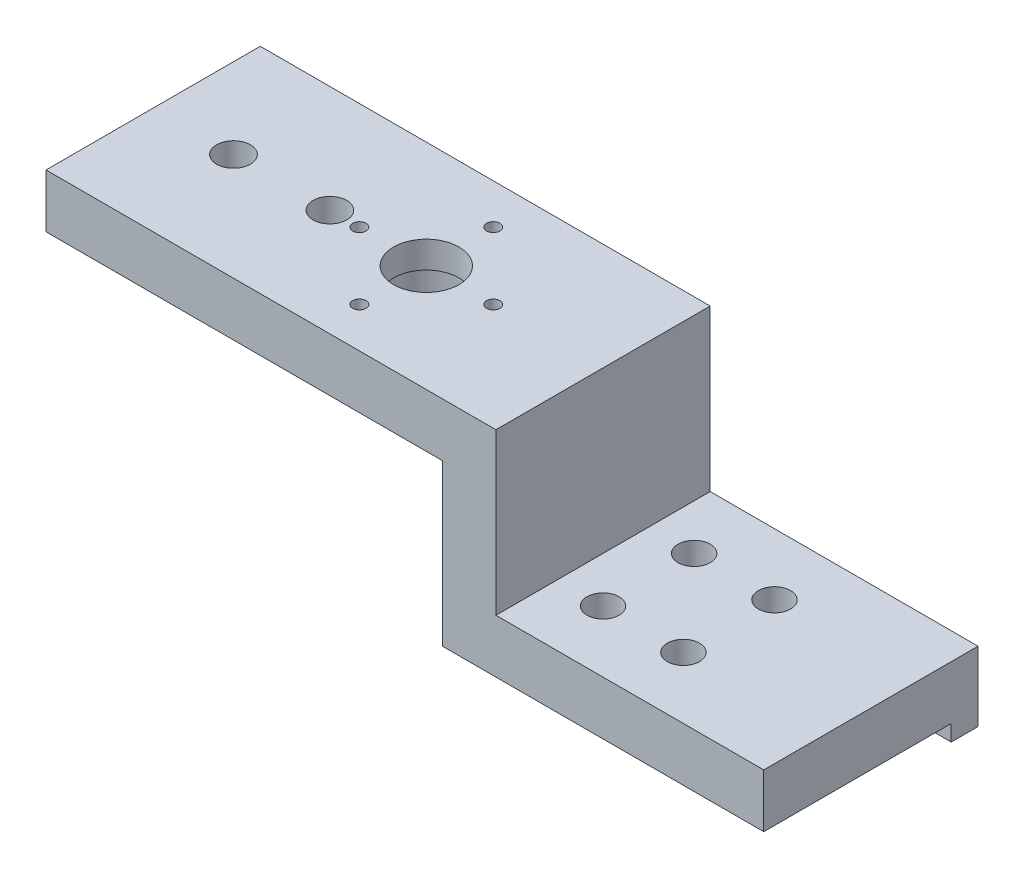
SolidWorks part; units mm, degrees
material "3.0205 (EN-AW 1200)"
ref_plane "Front Plane" through (0, 0, 0) normal (0, 0, 1) x (1, 0, 0)
ref_plane "Top Plane" through (0, 0, 0) normal (0, 1, 0) x (1, 0, 0)
ref_plane "Right Plane" through (0, 0, 0) normal (1, 0, 0) x (0, 0, -1)
sketch "Sketch1" plane through (0, 0, 0) normal (0, 1, 0) x (1, 0, 0)
  line L1 (-30, -20) -> (30, -20)
  line L2 (-30, -20) -> (-30, 20)
  line L3 (-30, 20) -> (30, 20)
  line L4 (30, -20) -> (30, 20)
  line L5 (0, 20) -> (0, -20) construction
  line L6 (-30, 0) -> (30, 0) construction
  point P0 (0, 0)
  dimension "D1" = 40
  dimension "D2" = 60
extrude "Boss-Extrude1" add sketch "Sketch1" along normal blind 10 contours L3 L4 L1 L2
sketch "Sketch2" plane through (0, 10, 0) normal (0, 1, 0) x (1, 0, 0)
  line L1 (-20, -20) -> (-30, -20)
  line L2 (-20, -20) -> (-20, 20)
  line L3 (-20, 20) -> (-30, 20)
  line L4 (-30, -20) -> (-30, 20)
  line L5 (-25, 20) -> (-25, -20) construction
  line L6 (-20, 0) -> (-30, 0) construction
  point P0 (-25, 0)
  dimension "D1" = 10
extrude "Boss-Extrude2" add sketch "Sketch2" along normal blind 30
sketch "Sketch3" plane through (-30, 0, 0) normal (-1, 0, 0) x (0, 0, 1)
  line L0 (-20, 40) -> (-20, 0) construction
  line L1 (-20, 30) -> (20, 30)
  line L2 (-20, 30) -> (-20, 40)
  line L3 (-20, 40) -> (20, 40)
  line L4 (20, 30) -> (20, 40)
  line L5 (0, 40) -> (0, 30) construction
  line L6 (-20, 35) -> (20, 35) construction
  point P0 (0, 35)
  dimension "D1" = 10
extrude "Boss-Extrude3" add sketch "Sketch3" along normal blind 74
sketch "Sketch4" plane through (0, 30, 0) normal (0, -1, 0) x (1, 0, 0)
  line L0 (-30, -20) -> (-30, 20) construction
  circle A0 centre (-53, 0) radius 6.1
  circle A1 centre (-71, 0) radius 3.15
  circle A2 centre (-89, 0) radius 3.15
  dimension "D4" = 6.3
  dimension "D5" = 6.3
  dimension "D6" = 12.2
  dimension "D1" = 23
  dimension "D2" = 18
  dimension "D3" = 18
extrude "Cut-Extrude1" cut sketch "Sketch4" against normal blind 74
sketch "Sketch5" plane through (0, 0, 0) normal (0, -1, 0) x (1, 0, 0)
  line L0 (0, 0) -> (-39.9909, 0) construction
  circle A2 centre (-11.5, 8.5) radius 3
  circle A3 centre (-11.5, -8.5) radius 3
  circle A4 centre (-89, 0) radius 3.15 construction
  circle A5 centre (3.5, 8.5) radius 3
  circle A6 centre (3.5, -8.5) radius 3
  dimension "D2" = 77.5
  dimension "D1" = 6
  dimension "D4" = 6
  dimension "D5" = 6
  dimension "D3" = 17
  dimension "D6" = 15
  dimension "D7" = 15
extrude "Cut-Extrude2" cut sketch "Sketch5" against normal blind 74
sketch "Sketch6" plane through (0, 30, 0) normal (0, -1, 0) x (1, 0, 0)
  circle A0 centre (-89, 0) radius 3.5
  circle A1 centre (-71, 0) radius 3.5
  dimension "D3" = 18
  dimension "D1" = 7
  dimension "D2" = 7
extrude "Cut-Extrude3" cut sketch "Sketch6" against normal blind 3
sketch "Sketch7" plane through (0, 30, 0) normal (0, -1, 0) x (1, 0, 0)
  circle A0 centre (-53, 0) radius 6.5
  circle A1 centre (-71, 0) radius 3.5 construction
  dimension "D1" = 13
  dimension "D2" = 18
extrude "Cut-Extrude4" cut sketch "Sketch7" against normal blind 5
hole_wizard "M3 Tapped Hole1" positions "Sketch8" profile "Sketch9" tap size "M3" standard "DIN" end condition through all
sketch "Sketch8" plane through (0, 40, 0) normal (0, 1, 0) x (1, 0, 0)
  circle A0 centre (-53, 0) radius 6.1 construction
  point P1 (-53, 12.5)
  dimension "D1" = 12.5
cosmetic thread "Hole Thread1" parameters "D2"=3
sketch "Sketch9" plane through (-53, 40, -12.5) normal (1, 0, 0) x (0, 0, 1)
  line L0 (0, 0) -> (0, 40)
  line L1 (0, 40) -> (1.25, 40)
  line L2 (1.25, 40) -> (1.25, 0)
  line L5 (1.25, 0) -> (0, 0)
  line L11 (0, -6.35) -> (0, 107.95) construction
  dimension "Thru Tap Drill Dia." = 2.5
  dimension "Thru Tap Drill Depth" = 40
pattern_circular "CirPattern1" count 4 over 360 about axis through (-53, 0, 0) along (0, 1, 0) of "M3 Tapped Hole1"
cosmetic thread "Hole Thread2" parameters "D2"=3
cosmetic thread "Hole Thread3" parameters "D2"=3
cosmetic thread "Hole Thread4" parameters "D2"=3
sketch "Sketch10" plane through (0, 0, 0) normal (0, -1, 0) x (1, 0, 0)
  line L0 (30, 20) -> (30, -20) construction
  line L1 (-30, -20) -> (30, -20)
  line L2 (-30, -20) -> (-30, -15)
  line L3 (-30, -15) -> (30, -15)
  line L4 (30, -20) -> (30, -15)
  dimension "D1" = 5
extrude "Boss-Extrude4" add sketch "Sketch10" along normal blind 3
equation "\"gap_gearbox\"=30"
equation "\"D1@Boss-Extrude2\"=\"gap_gearbox\""
equation "\"transmission_bearing_d_out\"=6.3"
equation "\"D5@Sketch4\"=\"transmission_bearing_d_out\""
equation "\"transmission_gear_dist\"=18"
equation "\"D2@Sketch4\"=\"transmission_gear_dist\""
equation "\"D3@Sketch6\"=\"transmission_gear_dist\""
